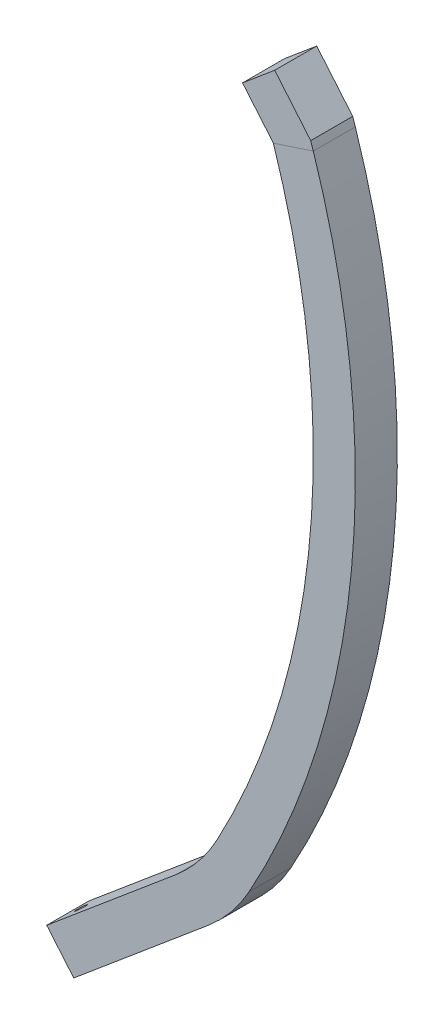
SolidWorks part; units mm, degrees
ref_plane "Ebene vorne" through (0, 0, 0) normal (0, 0, 1) x (1, 0, 0)
ref_plane "Ebene oben" through (0, 0, 0) normal (0, 1, 0) x (1, 0, 0)
ref_plane "Ebene rechts" through (0, 0, 0) normal (1, 0, 0) x (0, 0, -1)
sketch "Skizze1" plane through (0, 0, 0) normal (1, 0, 0) x (0, 0, -1)
  line L0 (0, 12) -> (-233.4212, 12) construction
  line L1 (-240, 65) -> (-230.7357, 72.7737)
  line L2 (0, 12) -> (-3.7358, 23.4037)
  line L3 (0, 12) -> (0, 39.1297) construction
  line L4 (0, 0) -> (-218.6687, 0) construction
  arc A0 (0, 12) -> (-240, 65) centre (-75.176, 241.4765) cw
  arc A1 (-3.7358, 23.4037) -> (-230.7357, 72.7737) centre (-75.176, 241.4765) cw
  dimension "D1" = 53
  dimension "D2" = 240
  dimension "D3" = 40
  dimension "D4" = 12
  dimension "D5" = 12
extrude "Aufsatz-Linear austragen1" add sketch "Skizze1" along normal blind 12
sketch "Skizze4" plane through (0, 0, 0) normal (1, 0, 0) x (0, 0, -1)
  line L0 (-230.7357, 72.7737) -> (-240, 65) construction
  line L2 (-3.7358, 23.4037) -> (6.769, 32.2183)
  line L3 (6.769, 32.2183) -> (14.4825, 23.0258)
  line L4 (14.4825, 23.0258) -> (2.2258, 12.7411)
  line L5 (-3.7358, 23.4037) -> (0, 12)
  arc A0 (0, 12) -> (2.2258, 12.7411) centre (-75.176, 241.4765) ccw
  arc A4 (-240, 65) -> (0, 12) centre (-75.176, 241.4765) ccw construction
  dimension "D1" = 16
  dimension "D2" = 12
extrude "Aufsatz-Linear austragen3" add sketch "Skizze4" along normal blind 12 separate body
sketch "Skizze5" plane through (12, 0, 0) normal (1, 0, 0) x (0, 0, -1)
  line L0 (-231.6625, 71.996) -> (-222.47, 79.7094)
  line L1 (-230.7357, 72.7737) -> (-232.109, 74.04) construction
  line L2 (-231.6625, 71.996) -> (-220.0923, 58.2072)
  line L3 (-230.7357, 72.7737) -> (-240, 65) construction
  line L4 (-222.47, 79.7094) -> (-210.8998, 65.9206)
  line L5 (-220.0923, 58.2072) -> (-192.9483, 44.5269)
  line L6 (-220.0923, 58.2072) -> (-211.3409, 65.5505) construction
  line L7 (-210.8998, 65.9206) -> (-192.9483, 44.5269)
  arc A6 (-230.7357, 72.7737) -> (-3.7358, 23.4037) centre (-75.176, 241.4765) ccw construction
  dimension "D1" = 12
  dimension "D2" = 1.2
  dimension "D3" = 18
extrude "Aufsatz-Linear austragen4" add sketch "Skizze5" against normal up to surface (12 mm away) up to face at (0, 27.378, 122.107)
sketch "Skizze6" plane through (12, 0, 0) normal (1, 0, 0) x (0, 0, -1)
  line L0 (-231.6625, 71.996) -> (-199.5106, 33.6789)
  line L1 (-199.5106, 33.6789) -> (-204.3677, 29.6033)
  line L2 (-204.3677, 29.6033) -> (-240, 65)
  line L3 (-240, 65) -> (-231.6625, 71.996)
extrude "Schnitt-Linear austragen1" cut sketch "Skizze6" against normal through all
sketch "Skizze7" plane through (12, 0, 0) normal (1, 0, 0) x (0, 0, -1)
  line L0 (-222.47, 79.7094) -> (-229.5406, 88.1359)
  line L1 (-192.9483, 44.5269) -> (-222.47, 79.7094) construction
  line L2 (-229.5406, 88.1359) -> (-238.7332, 80.4225)
  line L3 (-238.7332, 80.4225) -> (-231.6625, 71.996)
  line M4 (-222.47, 79.7094) -> (-231.6625, 71.996)
  dimension "D1" = 11
extrude "Aufsatz-Linear austragen5" [suppressed] add sketch "Skizze7" against normal up to surface (12 mm away) contours L2 L3 L0 M4
fillet "Verrundung1" radius 50 2 edges at (6, 35.2854, 200.8587) (6, 44.5269, 192.9483)
sketch "Skizze8" [suppressed] plane through (0, -76.6111, 91.3015) normal (0, 0.6428, -0.766) x (-1, 0, 0)
  line L0 (-6, 215.0619) -> (-6, 184.7045) construction
  line L1 (0, 215.0619) -> (-12, 215.0619) construction
  circle A0 centre (-6, 210.0619) radius 1.55
  dimension "D2" = 3.1
  dimension "D1" = 5
extrude "Schnitt-Linear austragen2" [suppressed] cut sketch "Skizze8" against normal blind 6
sketch "Skizze9" plane through (0, 156.3205, 131.1685) normal (0, 0.766, 0.6428) x (1, 0, 0)
  line L0 (6, -119.1857) -> (6, -131.1857) construction
  line L1 (0, -119.1857) -> (12, -119.1857) construction
  line L2 (0, -131.1857) -> (12, -131.1857) construction
  line L3 (12, -125.1857) -> (0, -125.1857) construction
  line L4 (12, -119.1857) -> (12, -131.1857) construction
  line L5 (0, -119.1857) -> (0, -131.1857) construction
  line L7 (0, -131.1857) -> (12, -131.1857)
  line L8 (0, -131.1857) -> (0, -119.1857)
  line L9 (0, -119.1857) -> (12, -119.1857)
  line L10 (12, -131.1857) -> (12, -119.1857)
  line L11 (0, -131.1857) -> (12, -119.1857) construction
  line L12 (0, -119.1857) -> (12, -131.1857) construction
  point P12 (6, -125.1857)
  dimension "D1" = 12
extrude "Aufsatz-Linear austragen6" add sketch "Skizze9" along normal blind 11
sketch "Skizze10" plane through (0, 16.6449, -19.8366) normal (0, 0.6428, -0.766) x (-1, 0, 0)
  line L0 (-6, 20.3296) -> (-6, 8.3296) construction
  line L1 (-12, 20.3296) -> (0, 20.3296) construction
  line L2 (-12, 8.3296) -> (0, 8.3296) construction
  line L4 (-11.9, 8.4296) -> (-0.1, 8.4296)
  line L5 (-11.9, 8.4296) -> (-11.9, 20.2296)
  line L6 (-11.9, 20.2296) -> (-0.1, 20.2296)
  line L7 (-0.1, 8.4296) -> (-0.1, 20.2296)
  line L8 (-11.9, 8.4296) -> (-0.1, 20.2296) construction
  line L9 (-11.9, 20.2296) -> (-0.1, 8.4296) construction
  circle A0 centre (-6, 14.3296) radius 9.0363
  point P6 (-6, 14.3296)
  dimension "D1" = 11.8
extrude "Schnitt-Linear austragen3" [suppressed] cut sketch "Skizze10" against normal blind 10
sketch "Skizze11" plane through (0, -76.6111, 91.3015) normal (0, 0.6428, -0.766) x (-1, 0, 0)
  line L0 (-6, 215.0619) -> (-6, 204.6824) construction
  line L1 (-12, 215.0619) -> (0, 215.0619) construction
  circle A0 centre (-6, 210.0619) radius 1.55
  dimension "D1" = 3.1
  dimension "D2" = 5
extrude "Schnitt-Linear austragen4" cut sketch "Skizze11" against normal through all
chamfer "Fase1" [suppressed] distance 0.1 angle 45
move or copy body "Körper-Verschieben/Kopieren2" bodies to move or copy 112 103 copy no rotation origin (-3.9694, 43.0579, 47.0273) rotation axis (0.5774, -0.5774, 0.5774) rotation angle 120
